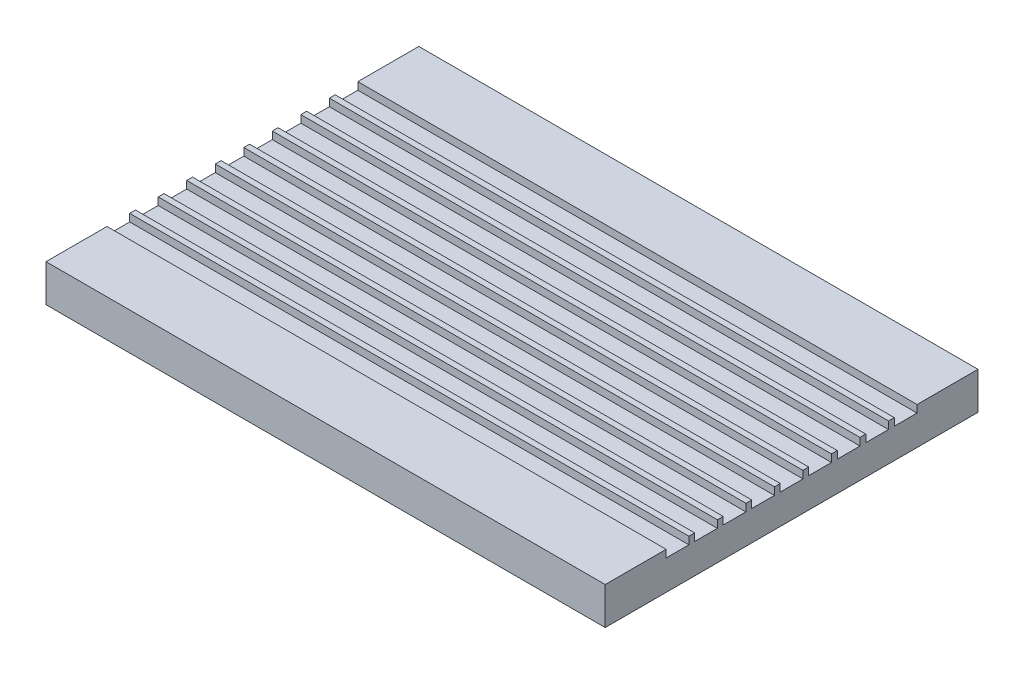
SolidWorks part; units mm, degrees
ref_plane "Płaszczyzna przednia" through (0, 0, 0) normal (0, 0, 1) x (1, 0, 0)
ref_plane "Płaszczyzna górna" through (0, 0, 0) normal (0, 1, 0) x (1, 0, 0)
ref_plane "Płaszczyzna prawa" through (0, 0, 0) normal (1, 0, 0) x (0, 0, -1)
sketch "Sketch1" plane through (0, 0, 0) normal (0, 1, 0) x (1, 0, 0)
  line L1 (-150, 100) -> (150, 100)
  line L2 (-150, 100) -> (-150, -100)
  line L3 (-150, -100) -> (150, -100)
  line L4 (150, 100) -> (150, -100)
  line L5 (-150, 100) -> (150, -100) construction
  line L6 (-150, -100) -> (150, 100) construction
  point P0 (0, 0)
  dimension "D1" = 200
  dimension "D2" = 300
extrude "Boss-Extrude1" add sketch "Sketch1" against normal blind 20
sketch "Sketch2" plane through (150, 0, 0) normal (1, 0, 0) x (0, 0, -1)
  line L1 (-67.3006, 0) -> (-55.1006, 0)
  line L2 (-67.3006, 0) -> (-67.3006, -4)
  line L3 (-67.3006, -4) -> (-55.1006, -4)
  line L4 (-55.1006, 0) -> (-55.1006, -4)
  line L5 (0, 31.1613) -> (0, -9.3239) construction
  line L6 (-100, 0) -> (100, 0) construction
  point P9 (-61.2006, 0)
  dimension "D1" = 12.2
  dimension "D2" = 4
  dimension "D3" = 61.2006
extrude "Cut-Extrude1" cut sketch "Sketch2" against normal through all
pattern_linear "LPattern1" count 9 spacing 15.3002 along (0, 0, -1) of "Cut-Extrude1"
other "CADCloud1" parameters "D1"=0
equation "\"D3@Sketch2\"=(\"no_of_tracks\"-1) * \"tracks_pitch\" / 2"
equation "\"D3@LPattern1\"=\"tracks_pitch\""
equation "\"D1@LPattern1\"=\"no_of_tracks\""
